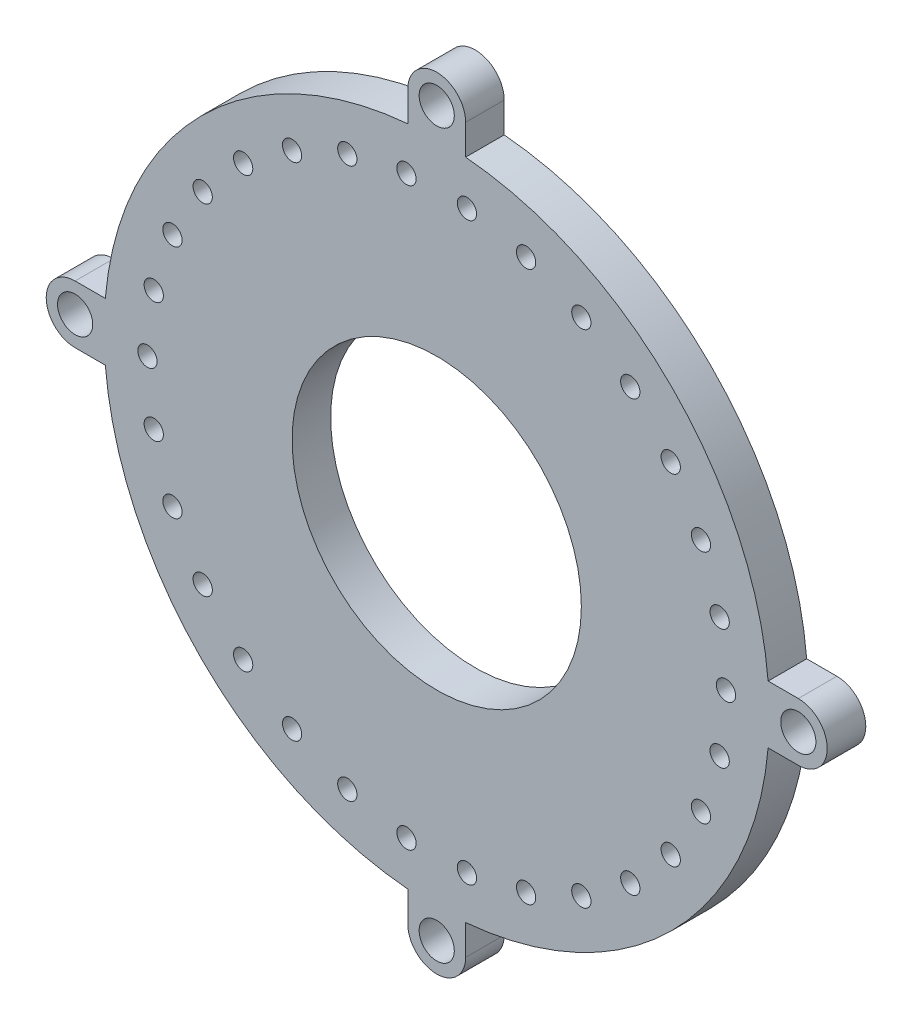
SolidWorks part; units mm, degrees
ref_plane "Front Plane" through (0, 0, 0) normal (0, 0, 1) x (1, 0, 0)
ref_plane "Top Plane" through (0, 0, 0) normal (0, 1, 0) x (1, 0, 0)
ref_plane "Right Plane" through (0, 0, 0) normal (1, 0, 0) x (0, 0, -1)
sketch "Sketch1" plane through (0, 0, 0) normal (0, 0, 1) x (1, 0, 0)
  circle A0 centre (0, 0) radius 54.7687
  dimension "D1" = 109.5375
extrude "Boss-Extrude1" add sketch "Sketch1" along normal blind 6.35
sketch "Sketch7" plane through (0, 0, 6.35) normal (0, 0, 1) x (1, 0, 0)
  line L0 (-59.5312, 4.7625) -> (-54.5613, 4.7625)
  line L1 (-59.5312, -4.7625) -> (-54.5613, -4.7625)
  line L2 (0, 0) -> (-59.5312, 0) construction
  line L3 (-4.7625, 59.5312) -> (-4.7625, 54.5613)
  line L4 (4.7625, 59.5312) -> (4.7625, 54.5613)
  line L5 (59.5312, 4.7625) -> (54.5613, 4.7625)
  line L6 (59.5312, -4.7625) -> (54.5613, -4.7625)
  line L7 (4.7625, -59.5312) -> (4.7625, -54.5613)
  line L8 (-4.7625, -59.5312) -> (-4.7625, -54.5613)
  arc A0 (-59.5312, 4.7625) -> (-59.5312, -4.7625) centre (-59.5312, 0) ccw
  circle A1 centre (0, 0) radius 54.7687 construction
  arc A2 (4.7625, 59.5312) -> (-4.7625, 59.5312) centre (0, 59.5312) ccw
  arc A3 (59.5312, -4.7625) -> (59.5312, 4.7625) centre (59.5312, 0) ccw
  arc A4 (-4.7625, -59.5312) -> (4.7625, -59.5312) centre (0, -59.5312) ccw
  circle A6 centre (0, 0) radius 54.7687
  point P27 (0, 0)
  dimension "D1" = 9.525
  dimension "D2" = 4
extrude "Boss-Extrude2" add sketch "Sketch7" against normal blind 6.35
sketch "Sketch8" plane through (0, 0, 6.35) normal (0, 0, 1) x (1, 0, 0)
  point P0 (-59.5312, 0)
  point P1 (0, 59.5312)
  point P3 (59.5312, 0)
  point P5 (0, -59.5312)
sketch "Sketch9" plane through (0, 0, 6.35) normal (0, 0, 1) x (1, 0, 0)
  point P0 (-59.5312, 0)
  point P3 (0, 59.5312)
  point P6 (59.5312, 0)
  point P9 (0, -59.5312)
hole_wizard "#1 (0.228) Diameter Hole1" positions "Sketch9" profile "Sketch10" hole size "#1" standard "ANSI Inch" end condition through all
sketch "Sketch10" plane through (-59.5312, 0, 6.35) normal (1, 0, 0) x (0, -1, 0)
  line L0 (0, 0) -> (0, 6.35)
  line L1 (0, 6.35) -> (2.8956, 6.35)
  line L2 (2.8956, 6.35) -> (2.8956, 0)
  line L5 (2.8956, 0) -> (0, 0)
  line L11 (0, -6.35) -> (0, 107.95) construction
  dimension "Thru Hole Dia." = 5.7912
  dimension "Thru Hole Depth" = 6.35
sketch "Sketch11" plane through (0, 0, 6.35) normal (0, 0, 1) x (1, 0, 0)
  circle A0 centre (0, 0) radius 47.625 construction
  circle A1 centre (-47.625, 0) radius 1.5875
  circle A2 centre (-46.5843, 9.9018) radius 1.5875
  circle A3 centre (-43.5076, 19.3708) radius 1.5875
  circle A4 centre (-38.5294, 27.9933) radius 1.5875
  circle A5 centre (-31.8673, 35.3923) radius 1.5875
  circle A6 centre (-23.8125, 41.2445) radius 1.5875
  circle A7 centre (-14.7169, 45.2941) radius 1.5875
  circle A8 centre (-4.9782, 47.3641) radius 1.5875
  circle A9 centre (4.9782, 47.3641) radius 1.5875
  circle A10 centre (14.7169, 45.2941) radius 1.5875
  circle A11 centre (23.8125, 41.2445) radius 1.5875
  circle A12 centre (31.8673, 35.3923) radius 1.5875
  circle A13 centre (38.5294, 27.9933) radius 1.5875
  circle A14 centre (43.5076, 19.3708) radius 1.5875
  circle A15 centre (46.5843, 9.9018) radius 1.5875
  circle A16 centre (47.625, 0) radius 1.5875
  circle A17 centre (46.5843, -9.9018) radius 1.5875
  circle A18 centre (43.5076, -19.3708) radius 1.5875
  circle A19 centre (38.5294, -27.9933) radius 1.5875
  circle A20 centre (31.8673, -35.3923) radius 1.5875
  circle A21 centre (23.8125, -41.2445) radius 1.5875
  circle A22 centre (14.7169, -45.2941) radius 1.5875
  circle A23 centre (4.9782, -47.3641) radius 1.5875
  circle A24 centre (-4.9782, -47.3641) radius 1.5875
  circle A25 centre (-14.7169, -45.2941) radius 1.5875
  circle A26 centre (-23.8125, -41.2445) radius 1.5875
  circle A27 centre (-31.8673, -35.3923) radius 1.5875
  circle A28 centre (-38.5294, -27.9933) radius 1.5875
  circle A29 centre (-43.5076, -19.3708) radius 1.5875
  circle A30 centre (-46.5843, -9.9018) radius 1.5875
  point P36 (0, 0)
  dimension "D1" = 95.25
  dimension "D2" = 3.175
  dimension "D3" = 30
extrude "Cut-Extrude1" cut sketch "Sketch11" against normal blind 3.175
sketch "Sketch12" plane through (0, 0, 6.35) normal (0, 0, 1) x (1, 0, 0)
  circle A0 centre (0, 0) radius 23.8125
  dimension "D1" = 47.625
extrude "Cut-Extrude2" cut sketch "Sketch12" against normal through all
